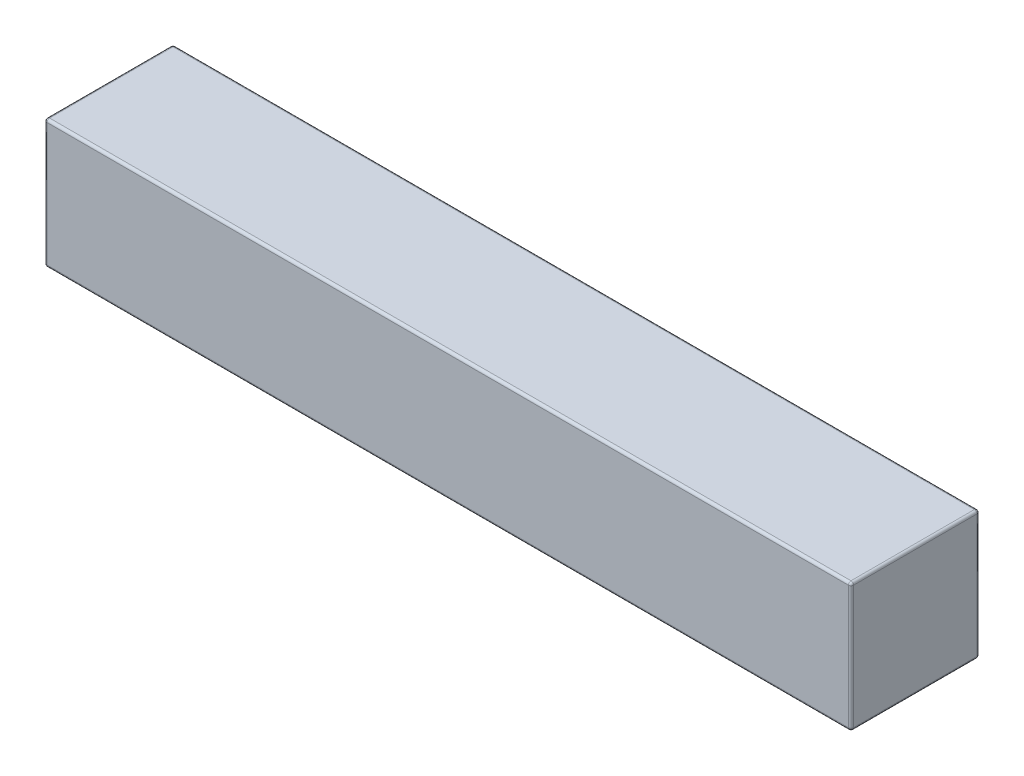
SolidWorks part; units mm, degrees
ref_plane "Front Plane" through (0, 0, 0) normal (0, 0, 1) x (1, 0, 0)
ref_plane "Top Plane" through (0, 0, 0) normal (0, 1, 0) x (1, 0, 0)
ref_plane "Right Plane" through (0, 0, 0) normal (1, 0, 0) x (0, 0, -1)
sketch "Sketch1" plane through (0, 0, 0) normal (0, 0, 1) x (1, 0, 0)
  line L1 (0, 0) -> (125.5, 0)
  line L2 (0, 0) -> (0, -20)
  line L3 (0, -20) -> (125.5, -20)
  line L4 (125.5, 0) -> (125.5, -20)
  dimension "D1" = 125.5
  dimension "D2" = 20
extrude "Boss-Extrude1" add sketch "Sketch1" along normal blind 20
fillet "Fillet1" radius 0.4 12 edges at (0, 0, 10) (0, -20, 10) (125.5, -20, 10) (125.5, 0, 10) (62.75, -20, 0) (125.5, -10, 0) (62.75, 0, 0) (0, -10, 0) (62.75, 0, 20) (125.5, -10, 20) (62.75, -20, 20) (0, -10, 20)
sketch "Sketch2" plane through (0, 0, 0) normal (0, 0, -1) x (-1, 0, 0)
  text T0 "125" font "Gill Sans Ultra Bold" height in points 48
extrude "Cut-Extrude1" cut sketch "Sketch2" against normal blind 0.6
